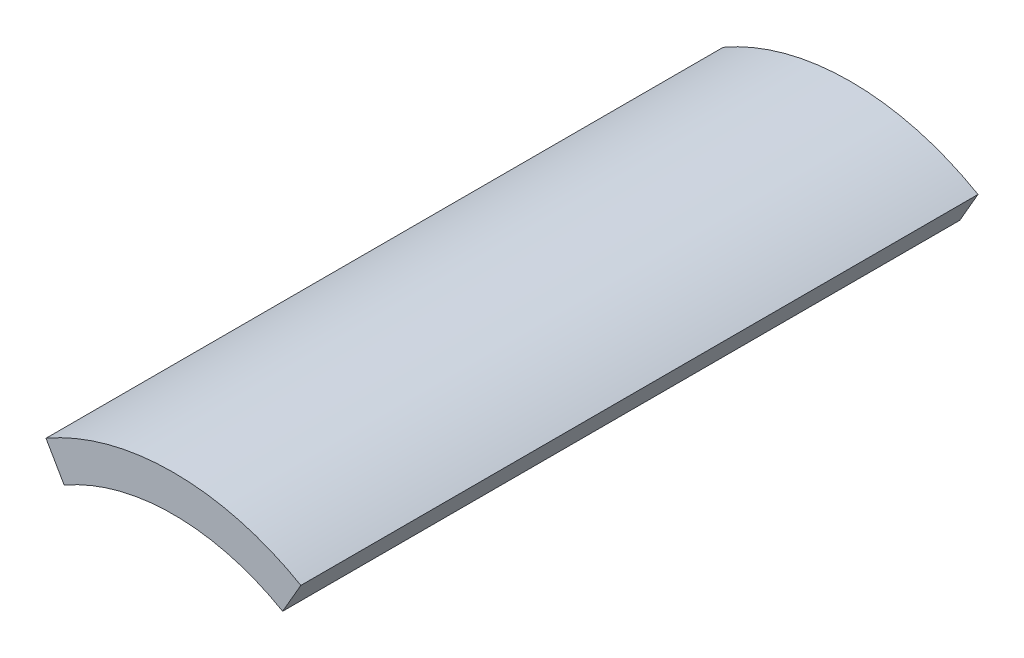
SolidWorks part; units mm, degrees
ref_plane "Front Plane" through (0, 0, 0) normal (0, 0, 1) x (1, 0, 0)
ref_plane "Top Plane" through (0, 0, 0) normal (0, 1, 0) x (1, 0, 0)
ref_plane "Right Plane" through (0, 0, 0) normal (1, 0, 0) x (0, 0, -1)
sketch "Sketch1" plane through (0, 0, 0) normal (0, 0, 1) x (1, 0, 0)
  line L1 (11.1125, 19.2474) -> (9.525, 16.4978)
  line L4 (0, 0) -> (0, 19.05) construction
  line L5 (-9.525, 16.4978) -> (-11.1125, 19.2474)
  line L6 (-11.1125, 19.2474) -> (-8.2371, 20.9075) construction
  line L7 (-9.525, 16.4978) -> (-6.13, 18.4579) construction
  line L8 (11.1125, 19.2474) -> (3.2674, 23.7768) construction
  line L9 (9.525, 16.4978) -> (0.9576, 21.4442) construction
  arc A0 (-9.525, 16.4978) -> (9.525, 16.4978) centre (0, 0) cw
  arc A1 (-11.1125, 19.2474) -> (11.1125, 19.2474) centre (0, 0) cw
  dimension "D1" = 3.175
  dimension "D2" = 22.225
  dimension "D3" = 19.05
extrude "Boss-Extrude1" add sketch "Sketch1" along normal blind 59.055 contours A1 L5 A0 L1
